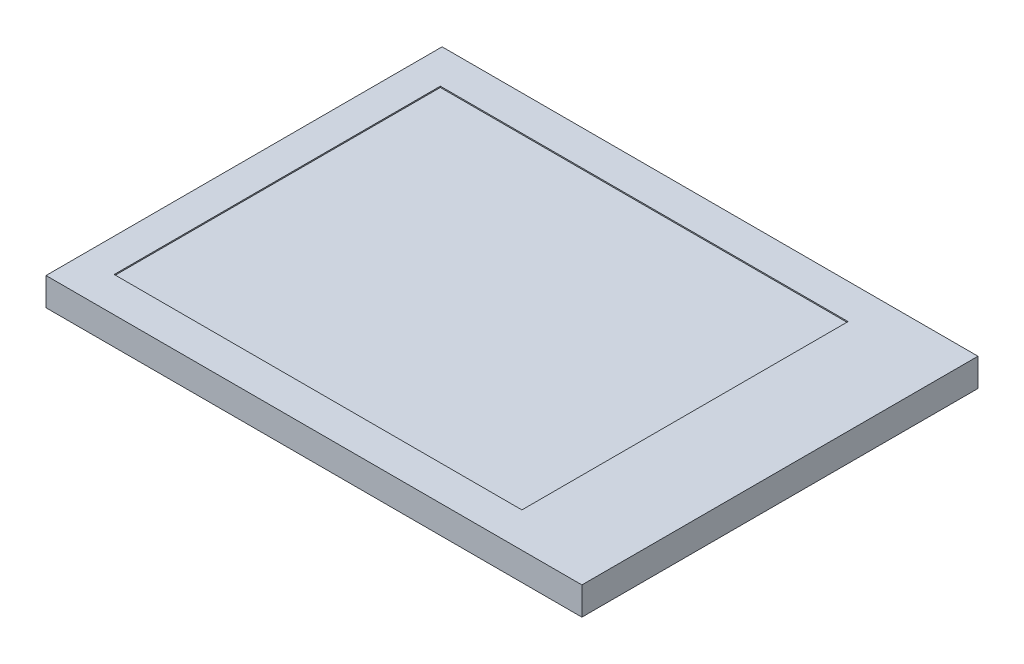
SolidWorks part; units mm, degrees
ref_plane "前视基准面" through (0, 0, 0) normal (0, 0, 1) x (1, 0, 0)
ref_plane "上视基准面" through (0, 0, 0) normal (0, 1, 0) x (1, 0, 0)
ref_plane "右视基准面" through (0, 0, 0) normal (1, 0, 0) x (0, 0, -1)
other "Configuration Table"
sketch "草图1" plane through (0, 0, 0) normal (0, 1, 0) x (1, 0, 0)
  line L0 (0, 17) -> (46, 17) construction
  line L1 (0, 0) -> (46, 0)
  line L2 (0, 0) -> (0, 34)
  line L3 (0, 34) -> (46, 34)
  line L4 (46, 0) -> (46, 34)
  line L6 (23, 34) -> (23, 0) construction
  dimension "D1" = 34
  dimension "D2" = 46
extrude "凸台-拉伸1" add sketch "草图1" along normal blind 2.4
sketch "草图2" plane through (0, 2.4, 0) normal (0, 1, 0) x (1, 0, 0)
  line L0 (2.85, 31) -> (37.85, 31)
  line L1 (2.85, 31) -> (2.85, 3)
  line L2 (2.85, 3) -> (37.85, 3)
  line L3 (37.85, 31) -> (37.85, 3)
  line L4 (23, 0) -> (23, 34) construction
  line L5 (0, 0) -> (46, 0) construction
  line L6 (46, 34) -> (0, 34) construction
  line L7 (23, 34) -> (46, 17) construction
  line L8 (46, 0) -> (46, 34) construction
  line L9 (46, 17) -> (0, 17) construction
  line L10 (0, 34) -> (0, 0) construction
  point P4 (37.85, 17)
  dimension "D1" = 35
  dimension "D2" = 28
  dimension "D3" = 2.85
extrude "切除-拉伸1" cut sketch "草图2" against normal blind 0.1
